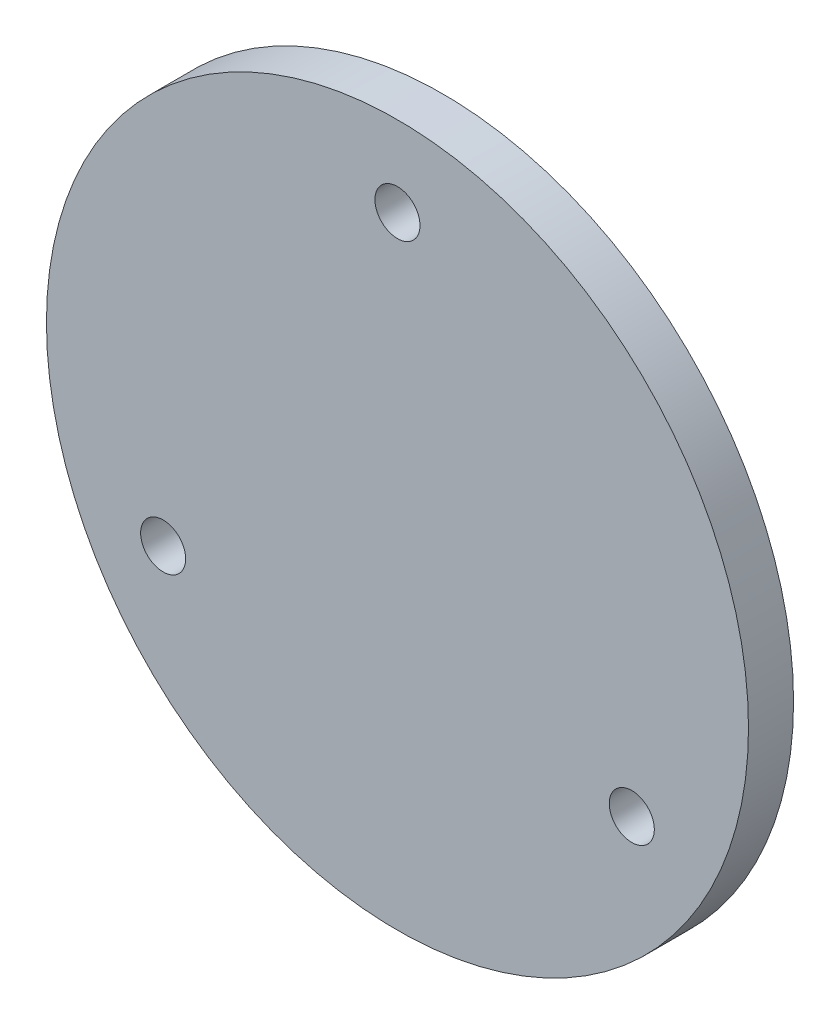
SolidWorks part; units mm, degrees
ref_plane "Front Plane" through (0, 0, 0) normal (0, 0, 1) x (1, 0, 0)
ref_plane "Top Plane" through (0, 0, 0) normal (0, 1, 0) x (1, 0, 0)
ref_plane "Right Plane" through (0, 0, 0) normal (1, 0, 0) x (0, 0, -1)
sketch "Sketch1" plane through (0, 0, 0) normal (0, 0, 1) x (1, 0, 0)
  circle A0 centre (0, 0) radius 49.4665
  dimension "D1" = 98.933
extrude "Boss-Extrude1" add sketch "Sketch1" along normal blind 6.35
sketch "Sketch2" [suppressed] plane through (0, 0, 6.35) normal (0, 0, 1) x (1, 0, 0)
  line L0 (-15.5, -30.74) -> (15.5, 0.26) construction
  line L1 (-15.5, 0.26) -> (15.5, 0.26)
  line L2 (-15.5, 0.26) -> (-15.5, -30.74)
  line L3 (-15.5, -30.74) -> (15.5, -30.74)
  line L4 (15.5, 0.26) -> (15.5, -30.74)
  point P4 (0, -15.24)
  point P5 (0, 0.26)
  dimension "D1" = 31
  dimension "D2" = 31
  dimension "D3" = 15.24
hole_wizard "Ø3.0mm Dowel Hole1" [suppressed] positions "Sketch3" profile "Sketch4" hole size "Ø3.0" standard "ANSI Metric"
sketch "Sketch3" [suppressed] plane through (0, 0, 6.35) normal (0, 0, 1) x (1, 0, 0)
  point P0 (15.5, 0.26)
  point P3 (-15.5, 0.26)
  point P6 (-15.5, -30.74)
  point P9 (15.5, -30.74)
sketch "Sketch4" plane through (15.5, 0.26, 6.35) normal (1, 0, 0) x (0, -1, 0)
  line L0 (0, 0) -> (0, 6.35)
  line L1 (0, 6.35) -> (1.5, 6.35)
  line L2 (1.5, 6.35) -> (1.5, 0)
  line L5 (1.5, 0) -> (0, 0)
  line L11 (0, -6.35) -> (0, 107.95) construction
  dimension "Thru Hole Dia." = 3
  dimension "Thru Hole Depth" = 6.35
sketch "Sketch5" [suppressed] plane through (0, 0, 6.35) normal (0, 0, 1) x (1, 0, 0)
  line L0 (-15.5, -30.74) -> (15.5, 0.26) construction
  line L1 (-21.15, 5.91) -> (21.15, 5.91)
  line L2 (-21.15, 5.91) -> (-21.15, -36.39)
  line L3 (-21.15, -36.39) -> (21.15, -36.39)
  line L4 (21.15, 5.91) -> (21.15, -36.39)
  line L5 (-21.15, 5.91) -> (21.15, -36.39) construction
  line L6 (-21.15, -36.39) -> (21.15, 5.91) construction
  circle A0 centre (0, -42.74) radius 3.175
  circle A1 centre (0, 12.26) radius 3.175
  point P0 (0, -15.24)
  point P7 (0, -15.24)
  dimension "D3" = 6.35
  dimension "D5" = 6.35
  dimension "D1" = 42.3
  dimension "D2" = 42.3
  dimension "D4" = 6.35
  dimension "D6" = 6.35
extrude "Cut-Extrude1" [suppressed] cut sketch "Sketch5" against normal through all contours A0 | A1
sketch "Sketch6" plane through (0, 0, 6.35) normal (0, 0, 1) x (1, 0, 0)
  line L0 (0, 38.1282) -> (-33.02, -19.0641) construction
  line L1 (-33.02, -19.0641) -> (33.02, -19.0641) construction
  line L2 (33.02, -19.0641) -> (0, 38.1282) construction
  line L3 (-33.02, -19.0641) -> (0, 0) construction
  line L4 (0, 0) -> (33.02, -19.0641) construction
  line L5 (0, 0) -> (0, 38.1282) construction
  circle A0 centre (0, 38.1282) radius 3.175
  circle A1 centre (-33.02, -19.0641) radius 3.175
  circle A2 centre (33.02, -19.0641) radius 3.175
  dimension "D1" = 6.35
  dimension "D2" = 66.04
  dimension "D3" = 60
  dimension "D4" = 60
extrude "Cut-Extrude2" cut sketch "Sketch6" against normal through all
sketch "Sketch8" [suppressed] plane through (0, 0, 6.35) normal (0, 0, 1) x (1, 0, 0)
  line L0 (-15.5, -30.74) -> (15.5, 0.26) construction
  circle A0 centre (0, -15.24) radius 11.049
  point P4 (0, -15.24)
  dimension "D1" = 22.098
extrude "Cut-Extrude3" [suppressed] cut sketch "Sketch8" against normal through all
